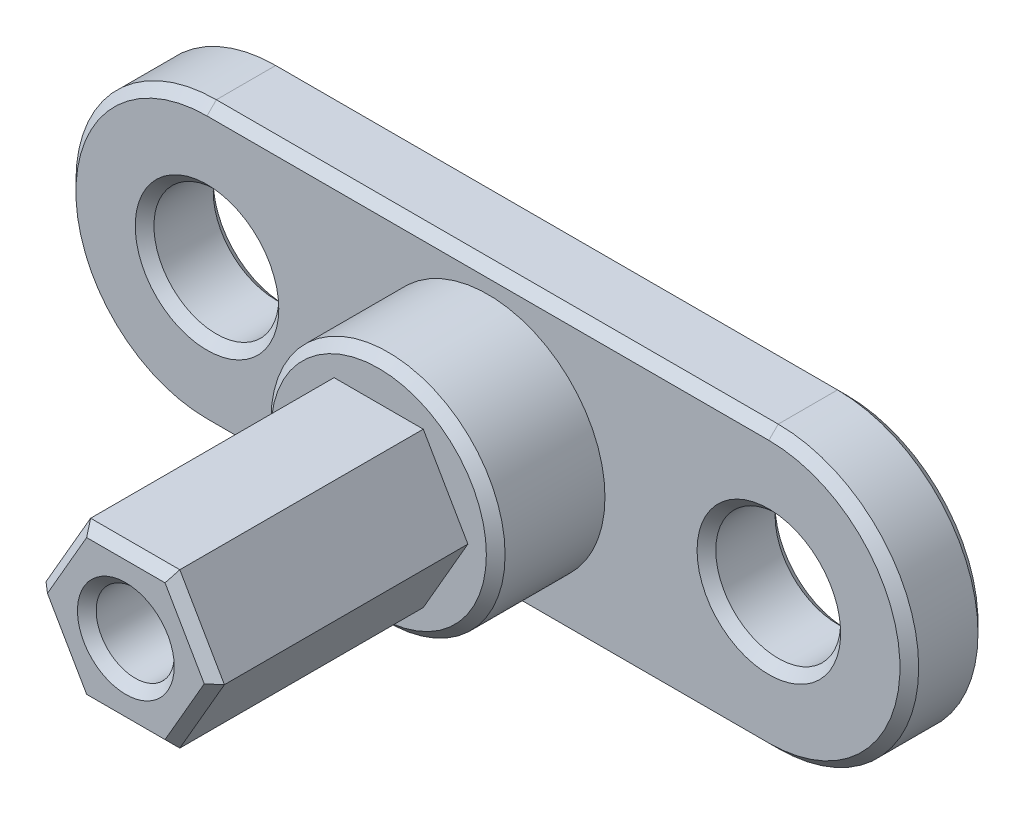
SolidWorks part; units mm, degrees
ref_plane "Front Plane" through (0, 0, 0) normal (0, 0, 1) x (1, 0, 0)
ref_plane "Top Plane" through (0, 0, 0) normal (0, 1, 0) x (1, 0, 0)
ref_plane "Right Plane" through (0, 0, 0) normal (1, 0, 0) x (0, 0, -1)
sketch "Sketch1" plane through (0, 0, 0) normal (0, 0, 1) x (1, 0, 0)
  line L1 (2.8579, -4.95) -> (5.7158, 0)
  line L2 (5.7158, 0) -> (2.8579, 4.95)
  line L3 (2.8579, 4.95) -> (-2.8579, 4.95)
  line L4 (-2.8579, 4.95) -> (-5.7158, 0)
  line L5 (-5.7158, 0) -> (-2.8579, -4.95)
  line L6 (-2.8579, -4.95) -> (2.8579, -4.95)
  circle A0 centre (0, 0) radius 4.95 construction
  dimension "D1" = 9.9
extrude "Boss-Extrude1" add sketch "Sketch1" along normal blind 16.2
sketch "Sketch2" plane through (0, 0, 0) normal (0, 0, 1) x (1, 0, 0)
  circle A0 centre (0, 0) radius 7.5
  dimension "D1" = 15
extrude "Boss-Extrude2" add sketch "Sketch2" against normal blind 7
sketch "Sketch3" plane through (0, 0, -7) normal (0, 0, -1) x (-1, 0, 0)
  line L0 (-18, 0) -> (18, 0) construction
  line L1 (-18, 9) -> (18, 9)
  line L2 (-18, -9) -> (18, -9)
  arc A0 (-18, 9) -> (-18, -9) centre (-18, 0) ccw
  arc A1 (18, -9) -> (18, 9) centre (18, 0) ccw
  circle A2 centre (-18, 0) radius 4
  circle A3 centre (18, 0) radius 4
  point P2 (0, 0)
  dimension "D3" = 8
  dimension "D1" = 18
  dimension "D2" = 36
extrude "Boss-Extrude3" add sketch "Sketch3" along normal blind 5
sketch "Sketch4" plane through (0, 0, 16.2) normal (0, 0, 1) x (1, 0, 0)
  circle A0 centre (0, 0) radius 2.5
  dimension "D1" = 5
extrude "Cut-Extrude1" cut sketch "Sketch4" against normal blind 20
chamfer "Chamfer1" distance 0.6 angle 45 20 edges at (-4.2868, -2.475, 16.2) (-4.2868, 2.475, 16.2) (0, 4.95, 16.2) (4.2868, 2.475, 16.2) (4.2868, -2.475, 16.2) (0, -4.95, 16.2) (7.5, 0, 0) (14, 0, -7) (14, 0, -12) (-22, 0, -12) (-22, 0, -7) (27, 0, -12) (0, -9, -12) (0, 9, -12) (-27, 0, -12) (0, 9, -7) (27, 0, -7) (-27, 0, -7) (0, -9, -7) (2.5, 0, 16.2)
scale "Scale1" scale about centroid uniform scaling yes scale factor 0.4
